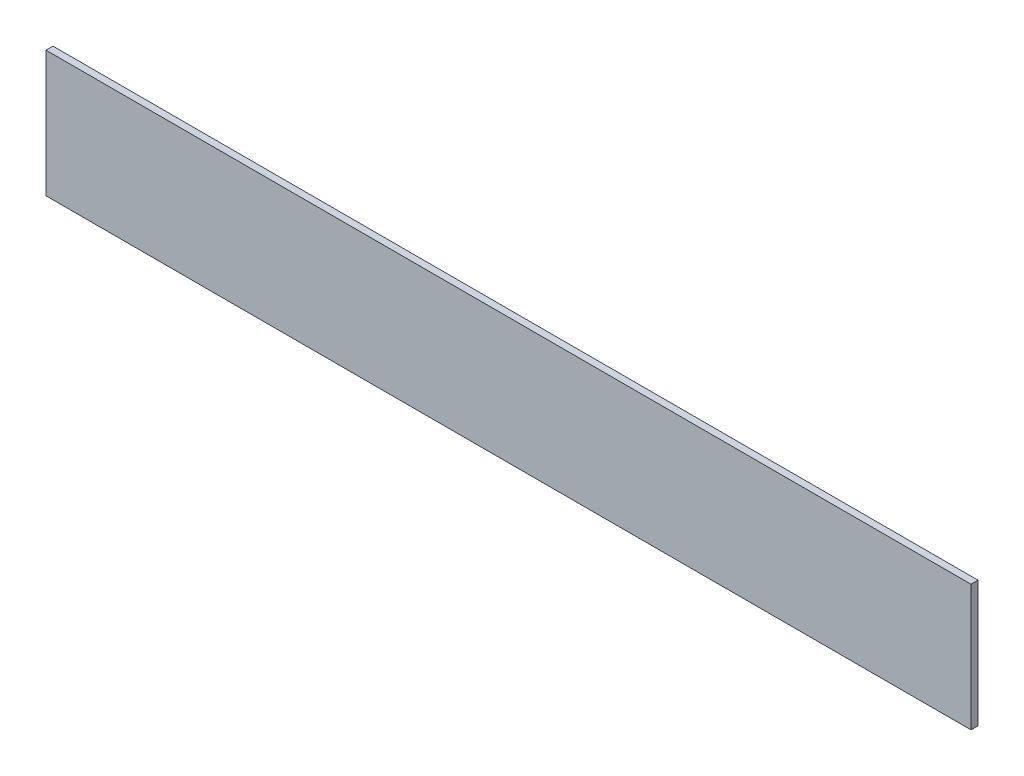
SolidWorks part; units mm, degrees
ref_plane "Front Plane" through (0, 0, 0) normal (0, 0, 1) x (1, 0, 0)
ref_plane "Top Plane" through (0, 0, 0) normal (0, 1, 0) x (1, 0, 0)
ref_plane "Right Plane" through (0, 0, 0) normal (1, 0, 0) x (0, 0, -1)
other "Configuration Table"
sketch "Sketch1" plane through (0, 0, 0) normal (0, 0, 1) x (1, 0, 0)
  line L1 (185, 552) -> (515, 552)
  line L2 (185, 552) -> (185, 597)
  line L3 (185, 597) -> (515, 597)
  line L4 (515, 552) -> (515, 597)
extrude "PACK_kalip_duvari_on_1" add sketch "Sketch1" against normal blind 2.5 from offset 235 separate body
